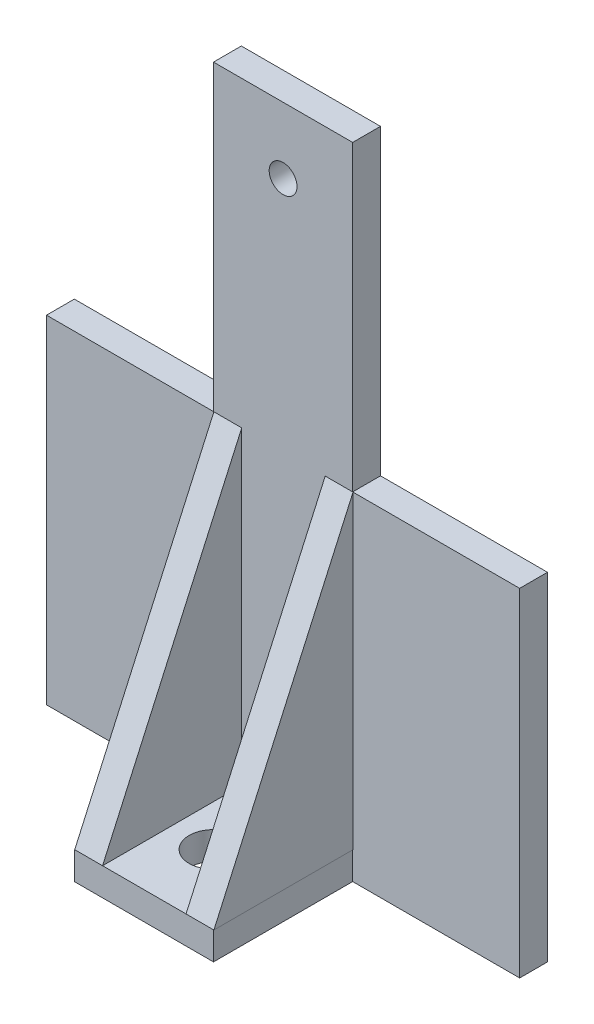
SolidWorks part; units mm, degrees
ref_plane "Plano frontal" through (0, 0, 0) normal (0, 0, 1) x (1, 0, 0)
ref_plane "Plano superior" through (0, 0, 0) normal (0, 1, 0) x (1, 0, 0)
ref_plane "Plano direito" through (0, 0, 0) normal (1, 0, 0) x (0, 0, -1)
sketch "Esboço1" plane through (0, 0, 0) normal (0, 0, 1) x (1, 0, 0)
  line L0 (4.5746, 15.5417) -> (16.5746, 15.5417)
  line L1 (-17.4254, -8.7083) -> (16.5746, -8.7083)
  line L2 (-17.4254, -8.7083) -> (-17.4254, 15.5417)
  line L3 (-5.4254, 37.2917) -> (4.5746, 37.2917)
  line L4 (16.5746, -8.7083) -> (16.5746, 15.5417)
  line L5 (-5.4254, -8.7083) -> (4.5746, -8.7083)
  line L6 (-5.4254, 15.5417) -> (-5.4254, 37.2917)
  line L7 (-5.4254, 37.2917) -> (4.5746, 37.2917)
  line L8 (4.5746, 15.5417) -> (4.5746, 37.2917)
  line L9 (-17.4254, -8.7083) -> (16.5746, -8.7083)
  line L10 (-17.4254, -8.7083) -> (-17.4254, 15.5417)
  line L11 (-17.4254, 15.5417) -> (-5.4254, 15.5417)
  line L12 (16.5746, -8.7083) -> (16.5746, 15.5417)
  circle A0 centre (-0.4254, -3.9583) radius 1
  circle A1 centre (-0.4254, 32.5417) radius 1
  dimension "D2" = 17
  dimension "D5" = 4.75
  dimension "D1" = 34
  dimension "D3" = 4.75
  dimension "D4" = 46
  dimension "D6" = 10
  dimension "D7" = 5
extrude "Ressalto-extrusão1" add sketch "Esboço1" along normal blind 2 contours L11 L2 L1 L4 L0 L8 L3 L6 A1 A0
sketch "Esboço2" plane through (0, 0, 2) normal (0, 0, 1) x (1, 0, 0)
  line L0 (16.5746, -8.7083) -> (16.5746, 15.5417) construction
  line L1 (-17.4254, -8.7083) -> (16.5746, -8.7083)
  line L2 (-17.4254, -8.7083) -> (-17.4254, -6.7083)
  line L3 (-17.4254, -6.7083) -> (16.5746, -6.7083)
  line L4 (16.5746, -8.7083) -> (16.5746, -6.7083)
  dimension "D1" = 2
extrude "Ressalto-extrusão2" add sketch "Esboço2" along normal blind 10
sketch "Esboço3" plane through (0, -6.7083, 0) normal (0, 1, 0) x (1, 0, 0)
  line L0 (-17.4254, -12) -> (16.5746, -2) construction
  line L1 (16.5746, -2) -> (16.5746, -12) construction
  line L2 (16.5746, -12) -> (-17.4254, -2) construction
  circle A0 centre (-0.4254, -7) radius 1.75
extrude "Corte-extrusão1" cut sketch "Esboço3" against normal blind 10
sketch "Esboço4" plane through (0, -6.7083, 0) normal (0, 1, 0) x (1, 0, 0)
  line L0 (16.5746, -2) -> (-17.4254, -2) construction
  line L1 (-17.4254, -12) -> (-5.3982, -12)
  line L2 (-17.4254, -12) -> (-17.4254, -2)
  line L3 (-17.4254, -2) -> (-5.3982, -2)
  line L4 (-5.3982, -12) -> (-5.3982, -2)
  line L6 (16.5746, -12) -> (4.5746, -12)
  line L7 (16.5746, -12) -> (16.5746, -2)
  line L8 (16.5746, -2) -> (4.5746, -2)
  line L9 (4.5746, -12) -> (4.5746, -2)
extrude "Corte-extrusão2" cut sketch "Esboço4" against normal blind 10
sketch "Esboço5" plane through (-5.3982, 0, 0) normal (-1, 0, 0) x (0, 0, 1)
  line L0 (12, -6.7083) -> (2, 15.5417)
  line L6 (2, 15.5417) -> (2, -6.7083)
  line L7 (2, -6.7083) -> (12, -6.7083)
extrude "Ressalto-extrusão3" add sketch "Esboço5" against normal blind 10
sketch "Esboço6" plane through (0, 0, 12) normal (0, 0, 1) x (1, 0, 0)
  line L1 (-3.3982, -6.7083) -> (2.6018, -6.7083)
  line L2 (-3.3982, -6.7083) -> (-3.3982, 15.5417)
  line L3 (-3.3982, 15.5417) -> (2.6018, 15.5417)
  line L4 (2.6018, -6.7083) -> (2.6018, 15.5417)
  line L5 (4.5746, 15.5417) -> (-5.3982, 15.5417) construction
  line L6 (-5.3982, -6.7083) -> (-5.3982, 15.5417) construction
  line L7 (4.6018, -6.7083) -> (4.6018, 15.5417) construction
  line L8 (4.5746, -6.7083) -> (-5.3982, -6.7083) construction
  dimension "D1" = 2
  dimension "D2" = 2
extrude "Corte-extrusão3" cut sketch "Esboço6" against normal blind 10
